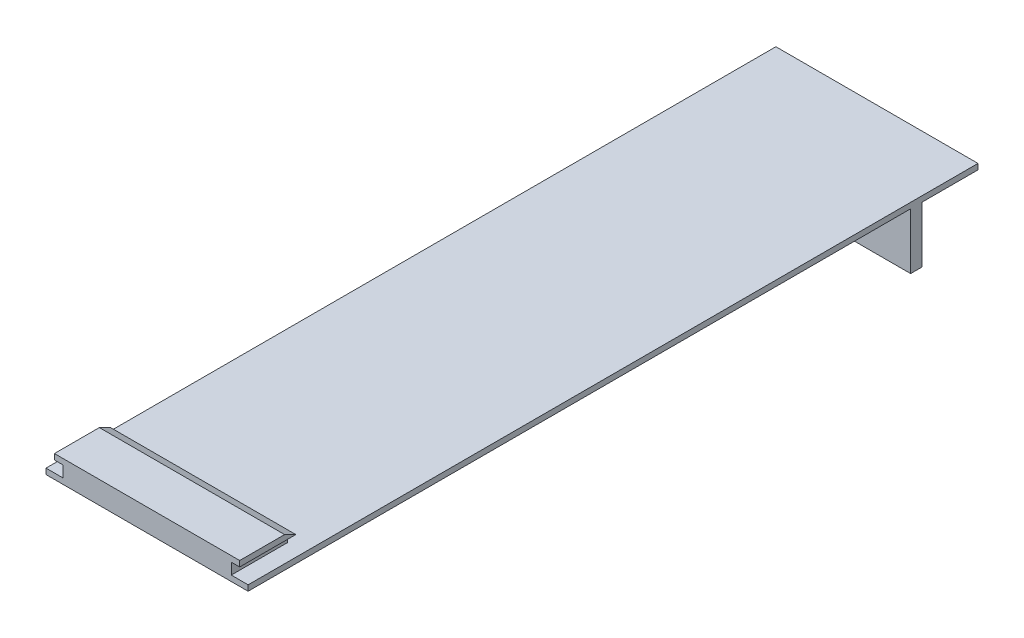
SolidWorks part; units mm, degrees
ref_plane "Front Plane" through (0, 0, 0) normal (0, 0, 1) x (1, 0, 0)
ref_plane "Top Plane" through (0, 0, 0) normal (0, 1, 0) x (1, 0, 0)
ref_plane "Right Plane" through (0, 0, 0) normal (1, 0, 0) x (0, 0, -1)
sketch "Sketch1" plane through (0, 0, 0) normal (0, 0, 1) x (1, 0, 0)
  line L1 (-18, -0.5) -> (18, -0.5)
  line L2 (-18, -0.5) -> (-18, 0.5)
  line L3 (-18, 0.5) -> (18, 0.5)
  line L4 (18, -0.5) -> (18, 0.5)
  line L5 (-18, -0.5) -> (18, 0.5) construction
  line L6 (-18, 0.5) -> (18, -0.5) construction
  point P0 (0, 0)
  dimension "D1" = 1
  dimension "D2" = 36
extrude "Boss-Extrude1" add sketch "Sketch1" along normal mid plane 130
ref_plane "Plane1" through (0, 0, 60) normal (0, 0, 1) x (1, 0, 0)
sketch "Sketch2" plane through (0, 0, 60) normal (0, 0, 1) x (1, 0, 0)
  line L0 (-15, 0.5) -> (-15, 2.5)
  line L1 (18, 0.5) -> (-18, 0.5) construction
  line L2 (-15, 2.5) -> (-16.5, 2.5)
  line L3 (-16.5, 2.5) -> (-16.5, 3.5)
  line L4 (-16.5, 3.5) -> (16.5, 3.5)
  line L5 (16.5, 3.5) -> (16.5, 2.5)
  line L6 (16.5, 2.5) -> (15, 2.5)
  line L7 (15, 2.5) -> (15, 0.5)
  line L8 (15, 0.5) -> (-15, 0.5)
  line L9 (0, 0) -> (0, 9.7402) construction
  dimension "D1" = 3
  dimension "D2" = 2
  dimension "D3" = 30
  dimension "D4" = 33
extrude "Boss-Extrude2" add sketch "Sketch2" along normal mid plane 10
sketch "Sketch3" plane through (0, -0.5, 0) normal (0, -1, 0) x (1, 0, 0)
  line L0 (18, 65) -> (18, -65) construction
  line L1 (-18, -55) -> (18, -55)
  line L2 (-18, -55) -> (-18, -53)
  line L3 (-18, -53) -> (18, -53)
  line L4 (18, -55) -> (18, -53)
  line L5 (-18, -55) -> (18, -53) construction
  line L6 (-18, -53) -> (18, -55) construction
  line L7 (-18, -65) -> (18, -65) construction
  line L8 (-18, 65) -> (-18, -65) construction
  point P0 (0, -54)
  dimension "D1" = 2
  dimension "D2" = 10
extrude "Boss-Extrude3" add sketch "Sketch3" along normal blind 10
sketch "Sketch4" plane through (16.5, 0, 0) normal (1, 0, 0) x (0, 0, -1)
  line L0 (-57, 3.5) -> (-55, 2.5)
  line L1 (-65, 3.5) -> (-55, 3.5) construction
  line L2 (-55, 2.5) -> (-55, 3.5)
  line L3 (-55, 3.5) -> (-57, 3.5)
  dimension "D1" = 2
extrude "Cut-Extrude1" cut sketch "Sketch4" against normal up to next
